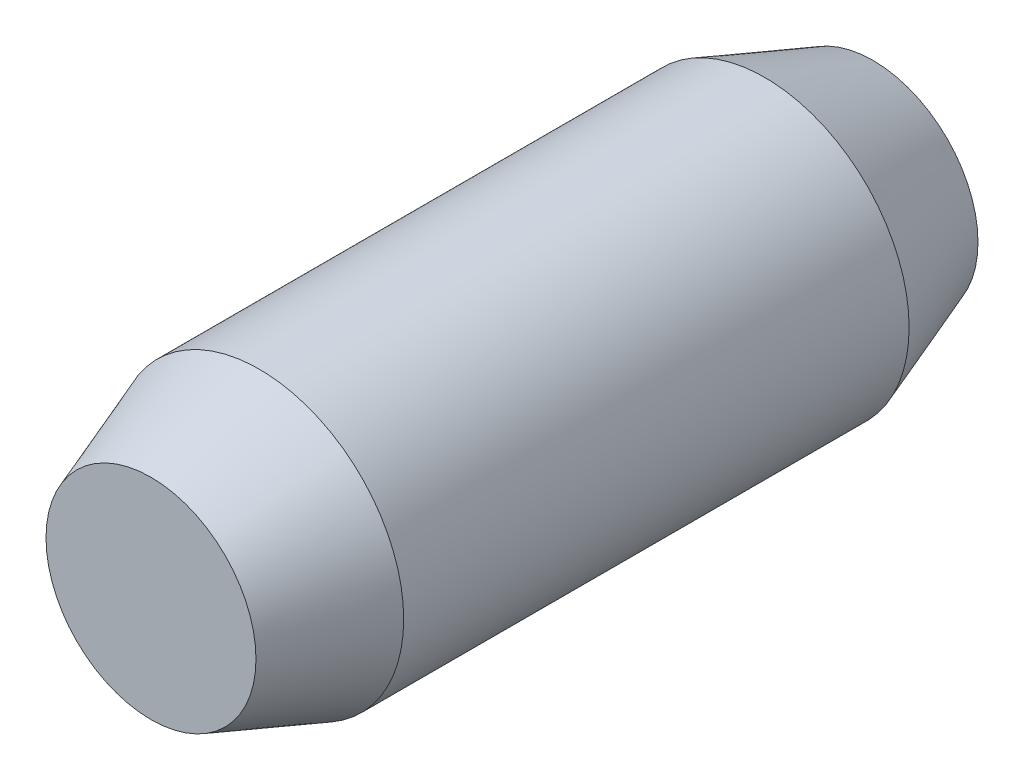
SolidWorks part; units mm, degrees
material "Beech"
ref_plane "Front Plane" through (0, 0, 0) normal (0, 0, 1) x (1, 0, 0)
ref_plane "Top Plane" through (0, 0, 0) normal (0, 1, 0) x (1, 0, 0)
ref_plane "Right Plane" through (0, 0, 0) normal (1, 0, 0) x (0, 0, -1)
sketch "Sketch1" plane through (0, 0, 0) normal (0, 0, 1) x (1, 0, 0)
  circle A0 centre (0, 0) radius 4
  dimension "D1" = 8
extrude "Extrude1" add sketch "Sketch1" along normal blind 20
chamfer "Chamfer2" distance 3 angle 20 1 edges at (4, 0, 20)
chamfer "Chamfer3" distance 3 angle 20 1 edges at (4, 0, 0)
